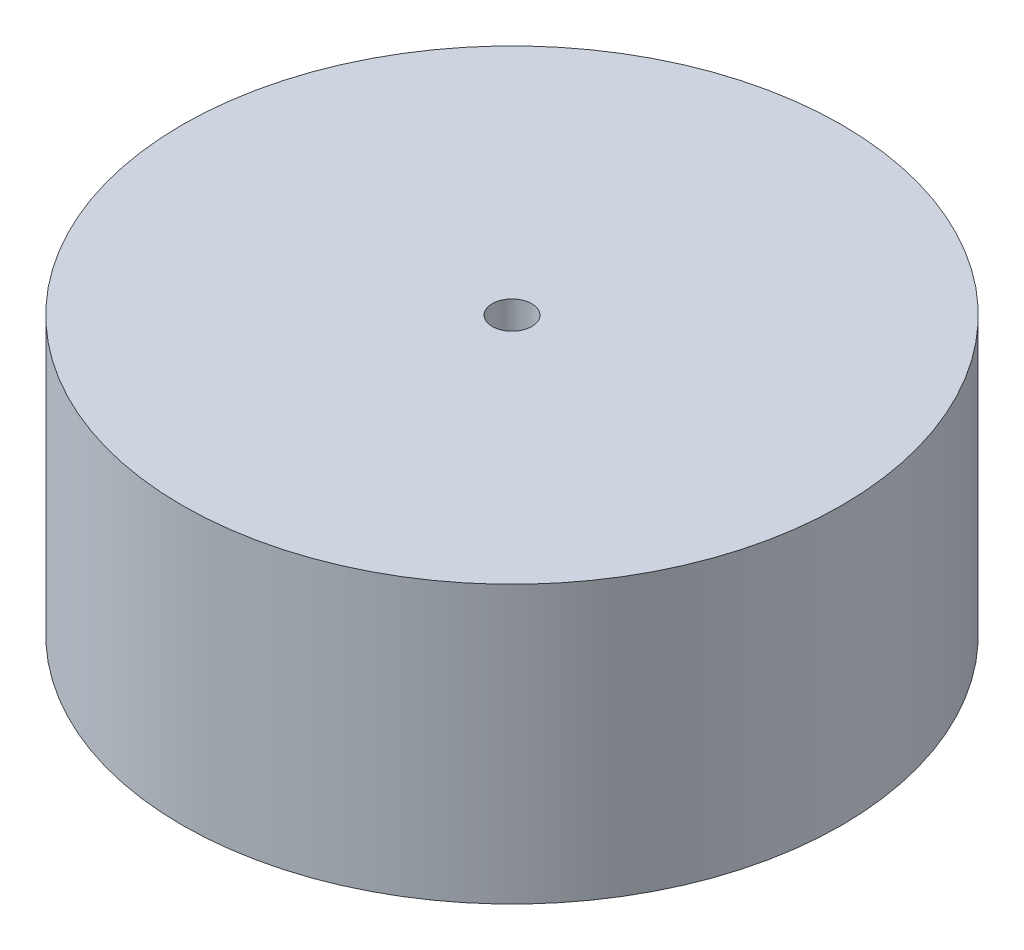
SolidWorks part; units mm, degrees
ref_plane "Plan de face" through (0, 0, 0) normal (0, 0, 1) x (1, 0, 0)
ref_plane "Plan de dessus" through (0, 0, 0) normal (0, 1, 0) x (1, 0, 0)
ref_plane "Plan de droite" through (0, 0, 0) normal (1, 0, 0) x (0, 0, -1)
sketch "Esquisse1" plane through (0, 0, 0) normal (0, 1, 0) x (1, 0, 0)
  circle A0 centre (0, 0) radius 25
  circle A1 centre (0, 0) radius 1.5
extrude "Extrusion1" add sketch "Esquisse1" along normal blind 21
